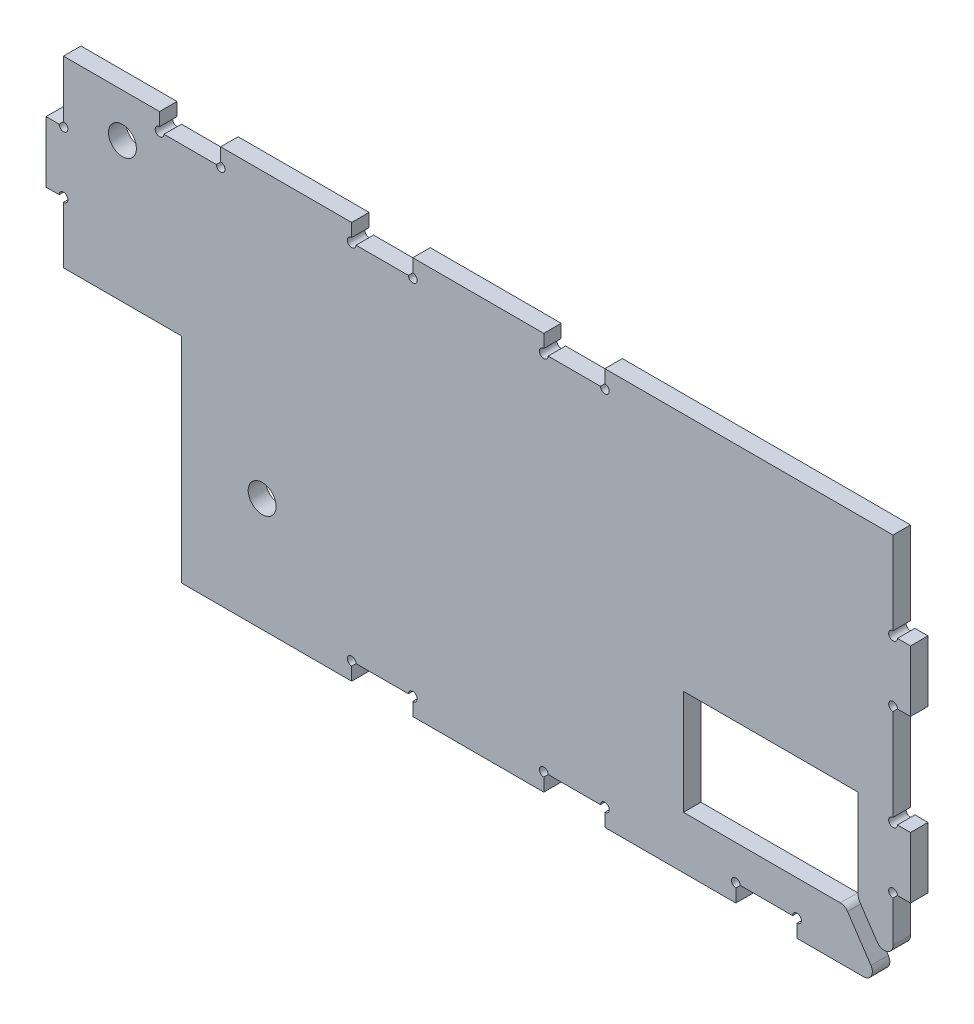
SolidWorks part; units mm, degrees
ref_plane "Front" through (0, 0, 0) normal (0, 0, 1) x (1, 0, 0)
ref_plane "Top" through (0, 0, 0) normal (0, 1, 0) x (1, 0, 0)
ref_plane "Right" through (0, 0, 0) normal (1, 0, 0) x (0, 0, -1)
sketch "草图1" plane through (0, 0, 0) normal (0, 0, 1) x (1, 0, 0)
  line L1 (0, 0) -> (95, 0)
  line L2 (0, 0) -> (0, 45.5)
  line L3 (0, 45.5) -> (95, 45.5)
  line L4 (95, 0) -> (95, 45.5)
  dimension "D1" = 95
  dimension "D2" = 45.5
extrude "凸台-拉伸1" add sketch "草图1" along normal blind 2
sketch "草图2" plane through (0, 0, 2) normal (0, 0, 1) x (1, 0, 0)
  line L0 (95, 45.5) -> (0, 45.5) construction
  line L1 (55, 45.5) -> (62, 45.5)
  line L2 (55, 45.5) -> (55, 43.5)
  line L3 (55, 43.5) -> (62, 43.5)
  line L4 (62, 45.5) -> (62, 43.5)
  line L6 (33, 45.5) -> (40, 45.5)
  line L7 (33, 45.5) -> (33, 43.5)
  line L8 (33, 43.5) -> (40, 43.5)
  line L9 (40, 45.5) -> (40, 43.5)
  line L10 (11, 45.5) -> (18, 45.5)
  line L11 (11, 45.5) -> (11, 43.5)
  line L12 (11, 43.5) -> (18, 43.5)
  line L13 (18, 45.5) -> (18, 43.5)
  line L19 (0, 0) -> (95, 0) construction
  line L25 (33, 0) -> (40, 0)
  line L26 (33, 0) -> (33, 2)
  line L27 (33, 2) -> (40, 2)
  line L28 (40, 0) -> (40, 2)
  line L29 (55, 0) -> (62, 0)
  line L30 (55, 0) -> (55, 2)
  line L31 (55, 2) -> (62, 2)
  line L32 (62, 0) -> (62, 2)
  line L33 (77, 0) -> (84, 0)
  line L34 (77, 0) -> (77, 2)
  line L35 (77, 2) -> (84, 2)
  line L36 (84, 0) -> (84, 2)
  dimension "D2" = 7
  dimension "D3" = 7
  dimension "D4" = 2
  dimension "D5" = 2
  dimension "D6" = 7
  dimension "D7" = 15
  dimension "D8" = 15
  dimension "D14" = 2
  dimension "D15" = 2
  dimension "D16" = 2
extrude "切除-拉伸1" cut sketch "草图2" against normal through all
sketch "草图3" plane through (0, 0, 2) normal (0, 0, 1) x (1, 0, 0)
  circle A0 centre (11, 43.5) radius 0.5
extrude "切除-拉伸2" cut sketch "草图3" against normal through all
sketch "草图5" plane through (0, 0, 2) normal (0, 0, 1) x (1, 0, 0)
  line L0 (0, 45.5) -> (0, 0) construction
  line L1 (0, 24.5) -> (13.5, 24.5)
  line L2 (0, 24.5) -> (0, 0)
  line L3 (0, 0) -> (13.5, 0)
  line L4 (13.5, 24.5) -> (13.5, 0)
  line L5 (0, 0) -> (33, 0) construction
  line L6 (11, 45.5) -> (0, 45.5) construction
  dimension "D1" = 21
  dimension "D2" = 13.5
extrude "切除-拉伸3" cut sketch "草图5" against normal through all
sketch "草图6" plane through (0, 0, 2) normal (0, 0, 1) x (1, 0, 0)
  line L0 (0, 45.5) -> (0, 24.5) construction
  line L1 (0, 38.5) -> (-2, 38.5)
  line L2 (0, 38.5) -> (0, 31.5)
  line L3 (0, 31.5) -> (-2, 31.5)
  line L4 (-2, 38.5) -> (-2, 31.5)
  line L5 (11, 45.5) -> (0, 45.5) construction
  line L7 (95, 0) -> (95, 45.5) construction
  line L8 (95, 35.5) -> (97, 35.5)
  line L9 (95, 35.5) -> (95, 28.5)
  line L10 (95, 28.5) -> (97, 28.5)
  line L11 (97, 35.5) -> (97, 28.5)
  line L12 (84, 0) -> (95, 0) construction
  line L13 (95, 17) -> (97, 17)
  line L14 (95, 17) -> (95, 10)
  line L15 (95, 10) -> (97, 10)
  line L16 (97, 17) -> (97, 10)
  line L17 (95, 45.5) -> (62, 45.5) construction
  dimension "D1" = 7
  dimension "D2" = 2
  dimension "D3" = 7
  dimension "D4" = 7
  dimension "D5" = 2
  dimension "D6" = 2
  dimension "D7" = 7
  dimension "D8" = 10
  dimension "D9" = 10
extrude "凸台-拉伸2" add sketch "草图6" against normal blind 2
sketch "草图4" plane through (0, 0, 2) normal (0, 0, 1) x (1, 0, 0)
  point P0 (18, 43.5)
  point P1 (33, 43.5)
  point P3 (40, 43.5)
  point P5 (55, 43.5)
  point P7 (62, 43.5)
  point P13 (84, 2)
  point P15 (77, 2)
  point P17 (62, 2)
  point P19 (55, 2)
  point P21 (40, 2)
  point P23 (33, 2)
  point P29 (0, 31.5)
  point P31 (95, 35.5)
  point P32 (0, 38.5)
  point P33 (95, 28.5)
  point P37 (95, 17)
  point P39 (95, 10)
pattern_sketch "草图阵列1" of "切除-拉伸2" driven by "草图4"
sketch "草图7" plane through (0, 0, 0) normal (0, 0, -1) x (-1, 0, 0)
  line L0 (-97, 10) -> (-97, 17) construction
  line L1 (-91, 18) -> (-71, 18)
  line L2 (-91, 18) -> (-91, 6)
  line L3 (-91, 6) -> (-71, 6)
  line L4 (-71, 18) -> (-71, 6)
  line L5 (-84, 0) -> (-95, 0) construction
  dimension "D1" = 20
  dimension "D2" = 12
  dimension "D3" = 6
  dimension "D4" = 6
extrude "切除-拉伸4" cut sketch "草图7" against normal through all
sketch "草图8" plane through (0, 0, 0) normal (0, 0, -1) x (-1, 0, 0)
  line L0 (-91, 7.5) -> (-95, 1.5)
  line L1 (-91, 18) -> (-91, 6) construction
  line L2 (-95, 0) -> (-95, 9.5) construction
  line L3 (-93.5, 0) -> (-89.5, 6)
  line L4 (-84, 0) -> (-95, 0) construction
  line L5 (-91, 6) -> (-71, 6) construction
  line L6 (-95, 1.5) -> (-95, 0)
  line L7 (-95, 0) -> (-93.5, 0)
  line L8 (-91, 7.5) -> (-91, 6)
  line L9 (-91, 6) -> (-89.5, 6)
  dimension "D1" = 1.5
  dimension "D2" = 1.5
  dimension "D3" = 1.5
extrude "切除-拉伸5" cut sketch "草图8" against normal through all
fillet "圆角1" radius 1 4 edges at (89.5, 6, 1) (93.5, 0, 1) (95, 1.5, 1) (91, 7.5, 1)
sketch "草图9" plane through (0, 0, 0) normal (0, 0, -1) x (-1, 0, 0)
  circle A0 centre (-6.75, 40.5) radius 1.6
  circle A1 centre (-22.75, 13) radius 1.6
extrude "切除-拉伸6" cut sketch "草图9" against normal blind 2
